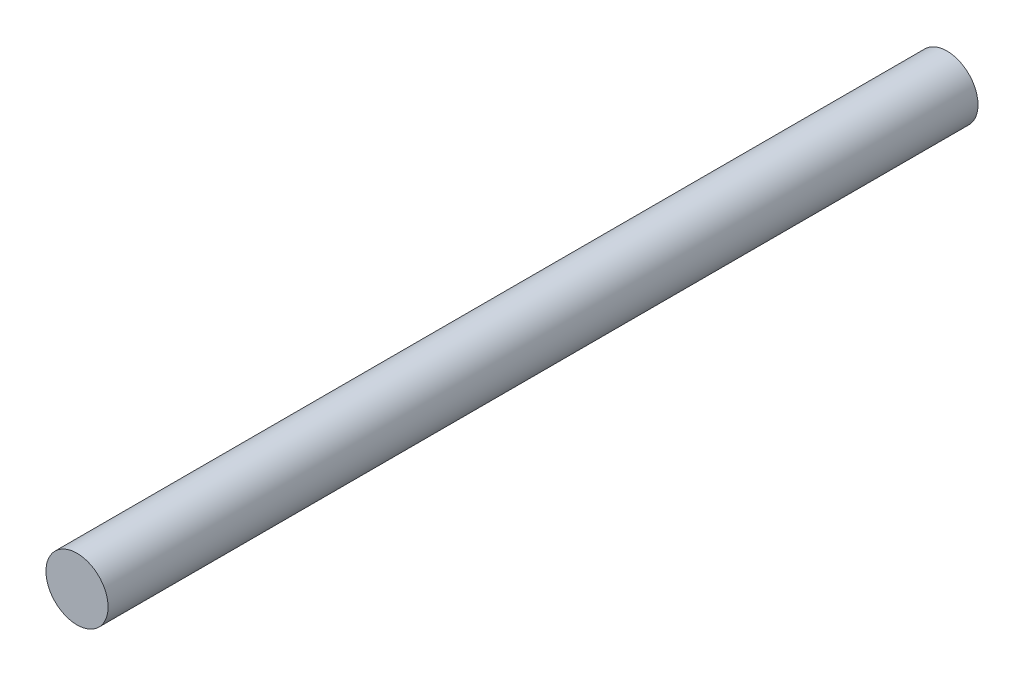
SolidWorks part; units mm, degrees
ref_plane "Front Plane" through (0, 0, 0) normal (0, 0, 1) x (1, 0, 0)
ref_plane "Top Plane" through (0, 0, 0) normal (0, 1, 0) x (1, 0, 0)
ref_plane "Right Plane" through (0, 0, 0) normal (1, 0, 0) x (0, 0, -1)
sketch "Sketch1" plane through (0, 0, 0) normal (0, 0, 1) x (1, 0, 0)
  circle A0 centre (0, 0) radius 5
  dimension "D1" = 10
extrude "Boss-Extrude1" add sketch "Sketch1" along normal blind 140
thread "Thread1" pitch 1.5 start angle 0, offset 0, length 130, pitch 1.5, diameter 10
ref_plane "Plane1" through (5, 0, 0) normal (0, -1, 0) x (1, 0, 0)
sketch "Thread Profile1" plane through (5, 0, 0) normal (0, -1, 0) x (1, 0, 0)
  line L0 (0, 0) -> (0, 1.5) construction
  line L11 (0, 0) -> (0, 1.3125)
  line L12 (0, 1.3125) -> (-0.8119, 0.8437)
  line L13 (-0.8119, 0.8437) -> (-0.8119, 0.4687)
  line L15 (-0.8119, 0.4687) -> (0, 0)
  line L17 (-0.8119, 0.6562) -> (0, 0.6562) construction
  point P2 (0, 0)
  dimension "Pitch" = 1.5
  dimension "Profile_Angle" = 60
  dimension "Profile_Land" = 0.375
  dimension "Profile_Height" = 0.8119
